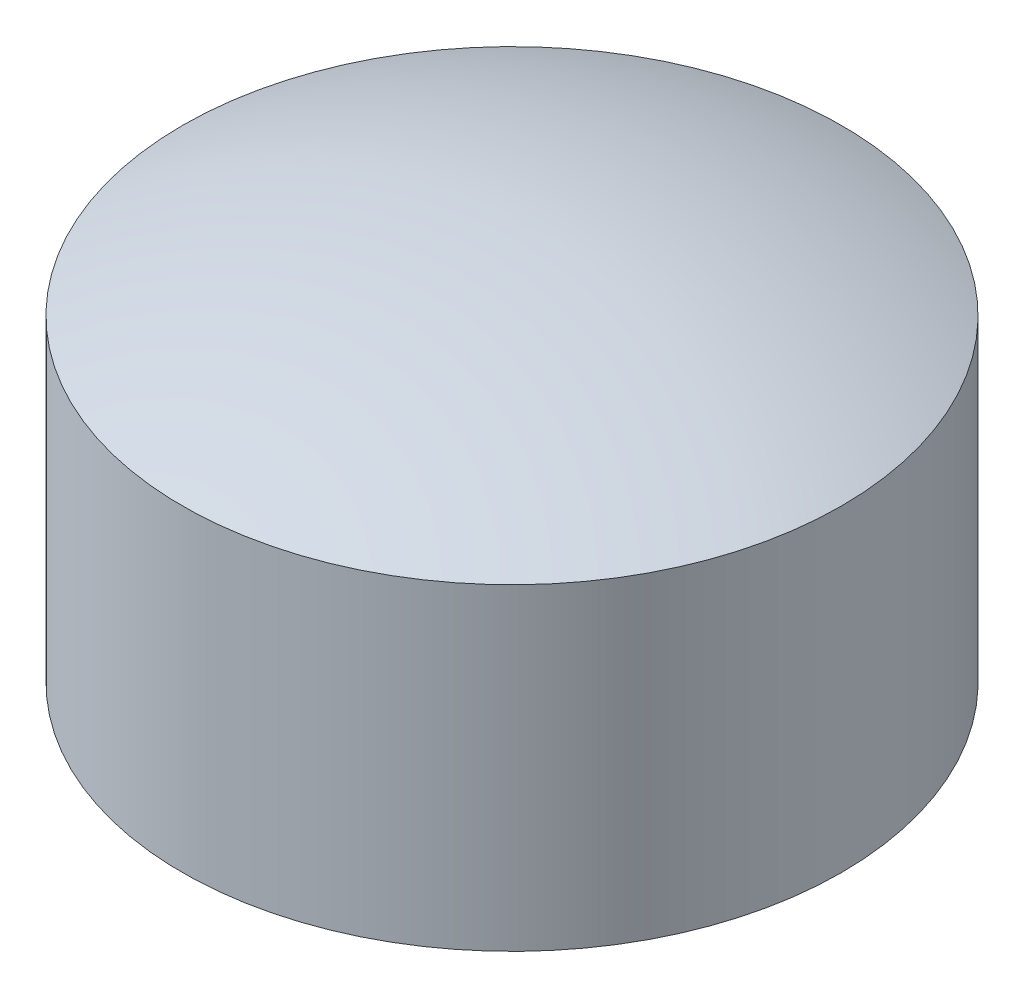
SolidWorks part; units mm, degrees
ref_plane "前基準面" through (0, 0, 0) normal (0, 0, 1) x (1, 0, 0)
ref_plane "上基準面" through (0, 0, 0) normal (0, 1, 0) x (1, 0, 0)
ref_plane "右基準面" through (0, 0, 0) normal (1, 0, 0) x (0, 0, -1)
sketch "草圖1" plane through (0, 0, 0) normal (0, 0, 1) x (1, 0, 0)
  line L0 (0, 0.5) -> (0, 1)
  line L1 (0, 0.5) -> (-0.5, 0.5)
  line L2 (-0.5, 0.5) -> (-0.5, 0)
  line L4 (-0.85, 0) -> (-0.5, 0)
  line L6 (0, 1.7551) -> (0, 0) construction
  line L7 (0, 0) -> (-0.85, 0) construction
  line L8 (-0.85, 0) -> (-0.85, 0.819)
  arc A0 (0, 1) -> (-0.85, 0.819) centre (0, -1.0862) ccw
  dimension "D4" = 0.5
  dimension "D2" = 2.0862
  dimension "D1" = 0.181
  dimension "D3" = 0.85
  dimension "D5" = 0.5
  dimension "D6" = 1
  dimension "D8" = 0.85
revolve "旋轉1" add sketch "草圖1" angle 360 about L6
cosmetic thread "裝飾螺紋線3" parameters "D1"=0.5, "D2"=1.6
